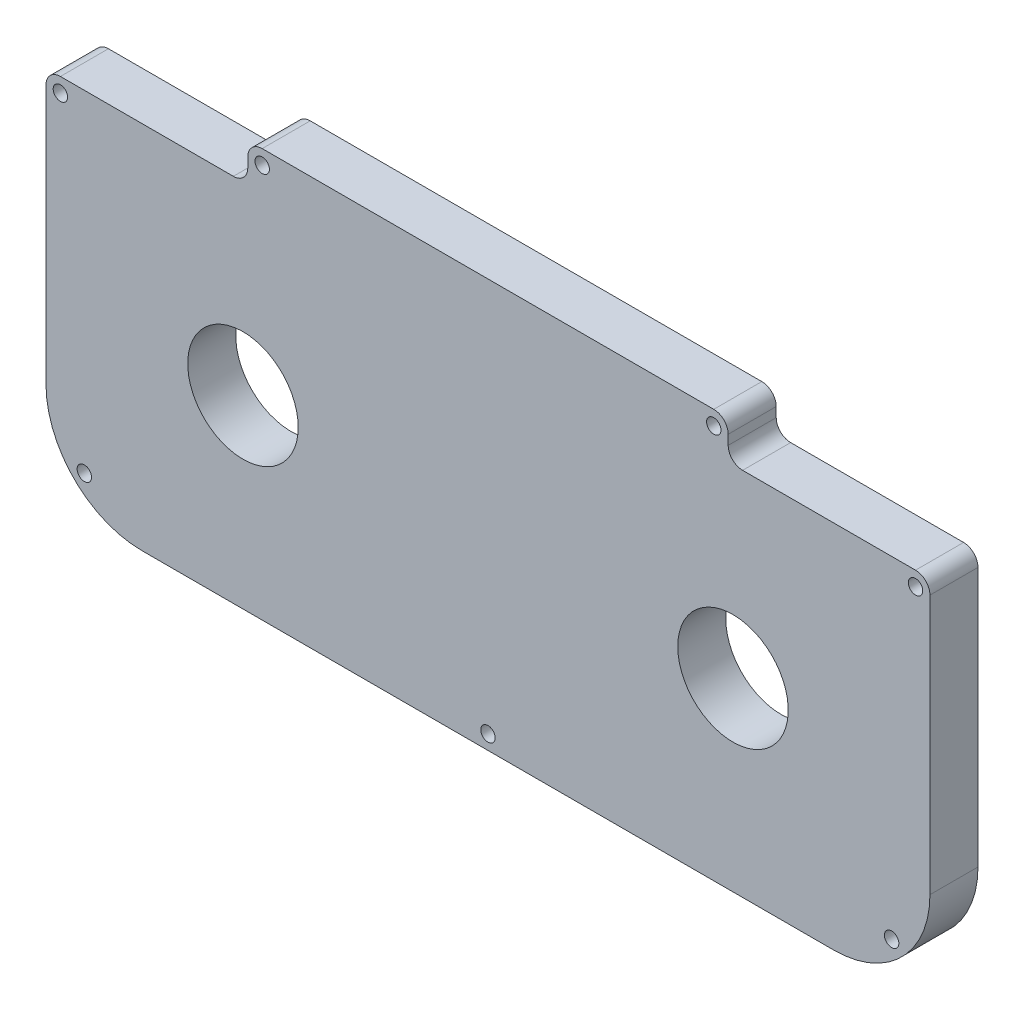
SolidWorks part; units mm, degrees
ref_plane "Front Plane" through (0, 0, 0) normal (0, 0, 1) x (1, 0, 0)
ref_plane "Top Plane" through (0, 0, 0) normal (0, 1, 0) x (1, 0, 0)
ref_plane "Right Plane" through (0, 0, 0) normal (1, 0, 0) x (0, 0, -1)
sketch "Sketch1" plane through (0, 0, 0) normal (0, 0, 1) x (1, 0, 0)
  line L0 (0, -55) -> (0, 55) construction
  line L8 (50, 39.5) -> (50, 37.5)
  line L9 (89, 34.5) -> (53, 34.5)
  line L10 (92, -22.5) -> (92, 31.5)
  line L11 (-72, -42.5) -> (72, -42.5)
  line L12 (-92, -22.5) -> (-92, 31.5)
  line L13 (-50, 39.5) -> (-50, 37.5)
  line L14 (-47, 42.5) -> (47, 42.5)
  line L15 (-89, 34.5) -> (-53, 34.5)
  circle A0 centre (51, -4) radius 11.5
  circle A15 centre (0, -39.5) radius 1.5
  circle A16 centre (84.0208, -34.5208) radius 1.5
  circle A17 centre (89, 31.5) radius 1.5
  circle A18 centre (47, 39.5) radius 1.5
  arc A19 (50, 39.5) -> (47, 42.5) centre (47, 39.5) ccw
  arc A20 (50, 37.5) -> (53, 34.5) centre (53, 37.5) ccw
  arc A21 (92, 31.5) -> (89, 34.5) centre (89, 31.5) ccw
  arc A22 (72, -42.5) -> (92, -22.5) centre (72, -22.5) ccw
  circle A23 centre (-47, 39.5) radius 1.5
  circle A24 centre (-89, 31.5) radius 1.5
  circle A25 centre (-84.0208, -34.5208) radius 1.5
  arc A26 (-92, -22.5) -> (-72, -42.5) centre (-72, -22.5) ccw
  arc A27 (-89, 34.5) -> (-92, 31.5) centre (-89, 31.5) ccw
  arc A28 (-47, 42.5) -> (-50, 39.5) centre (-47, 39.5) ccw
  arc A29 (-53, 34.5) -> (-50, 37.5) centre (-53, 37.5) ccw
  circle A30 centre (-51, -4) radius 11.5
  dimension "D1" = 23
extrude "Boss-Extrude1" add sketch "Sketch1" along normal blind 10
